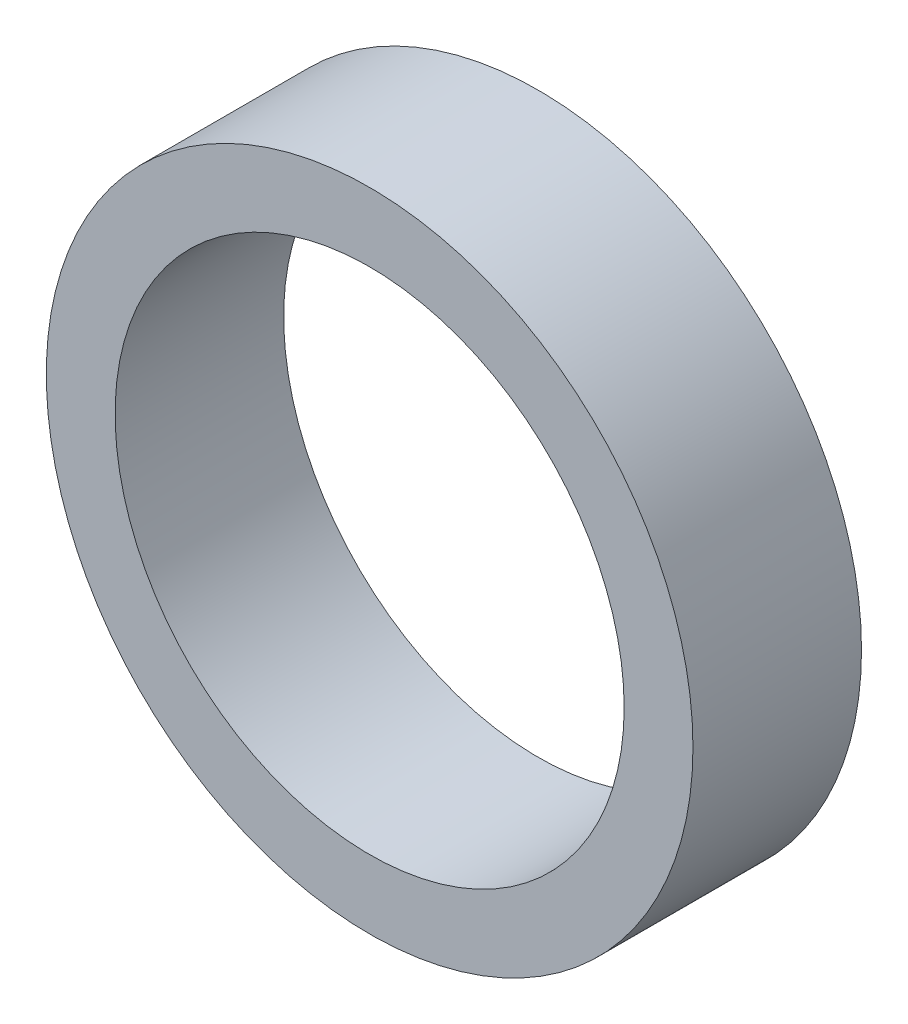
SolidWorks part; units mm, degrees
ref_plane "前视基准面" through (0, 0, 0) normal (0, 0, 1) x (1, 0, 0)
ref_plane "上视基准面" through (0, 0, 0) normal (0, 1, 0) x (1, 0, 0)
ref_plane "右视基准面" through (0, 0, 0) normal (1, 0, 0) x (0, 0, -1)
other "Configuration Table"
sketch "草图1" plane through (0, 0, 0) normal (0, 0, 1) x (1, 0, 0)
  circle A0 centre (0, 0) radius 7.4
  dimension "D1" = 14.8
extrude "拉伸-薄壁1" add sketch "草图1" along normal blind 4.9 thin contours A0
